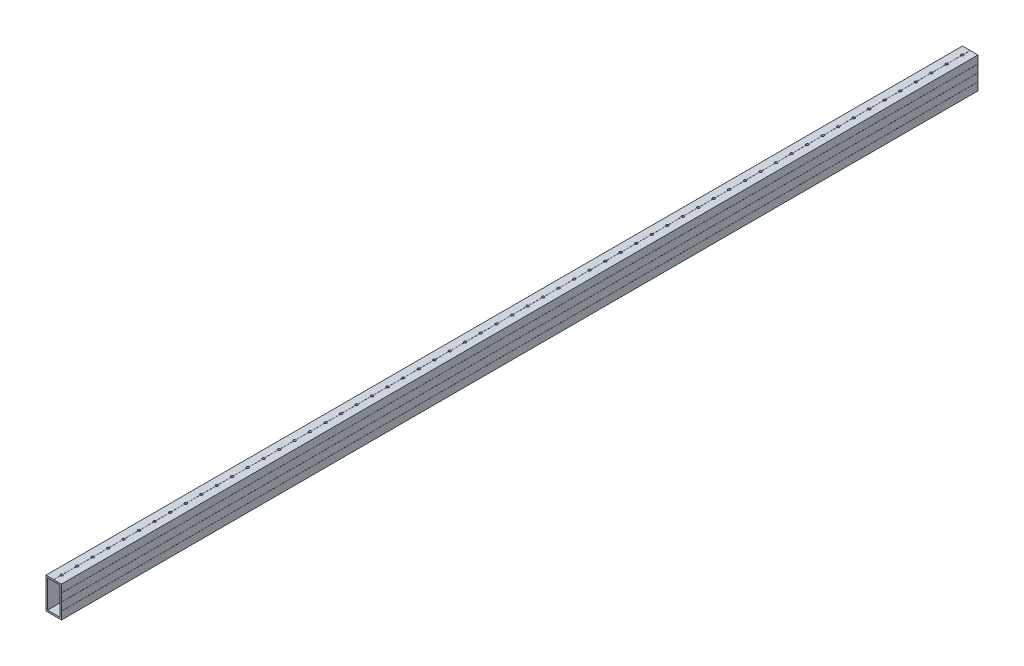
SolidWorks part; units mm, degrees
ref_plane "Front Plane" through (0, 0, 0) normal (0, 0, 1) x (1, 0, 0)
ref_plane "Top Plane" through (0, 0, 0) normal (0, 1, 0) x (1, 0, 0)
ref_plane "Right Plane" through (0, 0, 0) normal (1, 0, 0) x (0, 0, -1)
sketch "Sketch1" plane through (0, 0, 0) normal (0, 0, 1) x (1, 0, 0)
  line L0 (-10.16, -22.86) -> (-10.16, 22.86)
  line L1 (-12.7, -25.4) -> (12.7, -25.4)
  line L2 (-12.7, -25.4) -> (-12.7, 25.4)
  line L3 (-12.7, 25.4) -> (12.7, 25.4)
  line L4 (12.7, -25.4) -> (12.7, 25.4)
  line L5 (-12.7, -25.4) -> (12.7, 25.4) construction
  line L6 (-12.7, 25.4) -> (12.7, -25.4) construction
  line L7 (-10.16, 22.86) -> (10.16, 22.86)
  line L8 (10.16, -22.86) -> (10.16, 22.86)
  line L9 (-10.16, -22.86) -> (10.16, -22.86)
  point P0 (0, 0)
  dimension "D1" = 50.8
  dimension "D2" = 25.4
  dimension "D3" = 2.54
extrude "Boss-Extrude1" add sketch "Sketch1" against normal blind 1498.6
hole_wizard "#8 Clearance Hole1" positions "Sketch3" profile "Sketch4" hole size "#8" standard "ANSI Inch" end condition through all
sketch "Sketch3" plane through (0, 25.4, 0) normal (0, 1, 0) x (1, 0, 0)
  line L0 (12.7, 0) -> (-12.7, 0) construction
  line L1 (0, 12.7) -> (0, 38.1) construction
  point P0 (0, 12.7)
  point P14 (0, 38.1)
  point P15 (0, 63.5)
  point P16 (0, 88.9)
  point P17 (0, 114.3)
  point P18 (0, 139.7)
  point P19 (0, 165.1)
  point P20 (0, 190.5)
  point P21 (0, 215.9)
  point P22 (0, 241.3)
  point P23 (0, 266.7)
  point P24 (0, 292.1)
  point P25 (0, 317.5)
  point P26 (0, 342.9)
  point P27 (0, 368.3)
  point P28 (0, 393.7)
  point P29 (0, 419.1)
  point P30 (0, 444.5)
  point P31 (0, 469.9)
  point P32 (0, 495.3)
  point P33 (0, 520.7)
  point P34 (0, 546.1)
  point P35 (0, 571.5)
  point P36 (0, 596.9)
  point P37 (0, 622.3)
  point P38 (0, 647.7)
  point P39 (0, 673.1)
  point P40 (0, 698.5)
  point P41 (0, 723.9)
  point P42 (0, 749.3)
  point P43 (0, 774.7)
  point P44 (0, 800.1)
  point P45 (0, 825.5)
  point P46 (0, 850.9)
  point P47 (0, 876.3)
  point P48 (0, 901.7)
  point P49 (0, 927.1)
  point P50 (0, 952.5)
  point P51 (0, 977.9)
  point P52 (0, 1003.3)
  point P53 (0, 1028.7)
  point P54 (0, 1054.1)
  point P55 (0, 1079.5)
  point P56 (0, 1104.9)
  point P57 (0, 1130.3)
  point P58 (0, 1155.7)
  point P59 (0, 1181.1)
  point P60 (0, 1206.5)
  point P61 (0, 1231.9)
  point P62 (0, 1257.3)
  point P63 (0, 1282.7)
  point P64 (0, 1308.1)
  point P65 (0, 1333.5)
  point P66 (0, 1358.9)
  point P67 (0, 1384.3)
  point P68 (0, 1409.7)
  point P69 (0, 1435.1)
  point P70 (0, 1460.5)
  point P71 (0, 1485.9)
  dimension "D1" = 12.7
  dimension "D3" = 25.4
  dimension "D2" = 59
sketch "Sketch4" plane through (0, 25.4, -12.7) normal (1, 0, 0) x (0, 0, 1)
  line L0 (0, 0) -> (0, 50.8)
  line L1 (0, 50.8) -> (2.0701, 50.8)
  line L2 (2.0701, 50.8) -> (2.0701, 0)
  line L5 (2.0701, 0) -> (0, 0)
  line L11 (0, -6.35) -> (0, 107.95) construction
  dimension "Thru Hole Dia." = 4.1402
  dimension "Thru Hole Depth" = 50.8
sketch "Sketch2" plane through (0, 0, 0) normal (0, 0, 1) x (1, 0, 0)
  line L0 (-17.8561, 0) -> (30.0338, 0) construction
  line L1 (-26.3808, -12.7) -> (34.9233, -12.7) construction
  line L2 (0, -31.3757) -> (0, 40.0831) construction
  line L3 (-26.3808, 12.7) -> (34.9233, 12.7) construction
  line L4 (-12.7, 12.6238) -> (-12.7, 12.7762)
  line L5 (-12.7, 25.4) -> (-12.7, -25.4) construction
  line L6 (-12.7, 12.6238) -> (-12.6238, 12.7)
  line L7 (-12.6238, 12.7) -> (-12.7, 12.7762)
  line L8 (12.7, 12.6238) -> (12.6238, 12.7)
  line L9 (12.7, 12.6238) -> (12.7, 12.7762)
  line L10 (12.6238, 12.7) -> (12.7, 12.7762)
  line L11 (-12.6238, 0) -> (-12.7, 0.0762)
  line L12 (-12.7, -0.0762) -> (-12.7, 0.0762)
  line L13 (-12.7, -0.0762) -> (-12.6238, 0)
  line L14 (12.7, -0.0762) -> (12.6238, 0)
  line L15 (12.6238, 0) -> (12.7, 0.0762)
  line L16 (12.7, -0.0762) -> (12.7, 0.0762)
  line L17 (-12.6238, -12.7) -> (-12.7, -12.6238)
  line L18 (-12.7, -12.7762) -> (-12.7, -12.6238)
  line L19 (-12.7, -12.7762) -> (-12.6238, -12.7)
  line L20 (12.7, -12.7762) -> (12.6238, -12.7)
  line L21 (12.6238, -12.7) -> (12.7, -12.6238)
  line L22 (12.7, -12.7762) -> (12.7, -12.6238)
  line L23 (-12.6238, 12.7) -> (-12.6238, 0) construction
  line L24 (-0.0762, -25.4) -> (0.0762, -25.4)
  line L25 (-12.7, -25.4) -> (12.7, -25.4) construction
  line L26 (0.0762, -25.4) -> (0, -25.3238)
  line L27 (0, -25.3238) -> (-0.0762, -25.4)
  line L28 (0.0762, 25.4) -> (0, 25.3238)
  line L29 (-0.0762, 25.4) -> (0.0762, 25.4)
  line L30 (0, 25.3238) -> (-0.0762, 25.4)
  point P13 (-12.7, 12.7)
  point P18 (-0.0764, -25.4)
  point P37 (0, -25.4)
  point P39 (0, 0)
  dimension "D1" = 25.4
  dimension "D2" = 0.1524
  dimension "D4" = 12.7
  dimension "D5" = 0.1524
  dimension "D3" = 3
extrude "Cut-Extrude1" cut sketch "Sketch2" against normal through all
